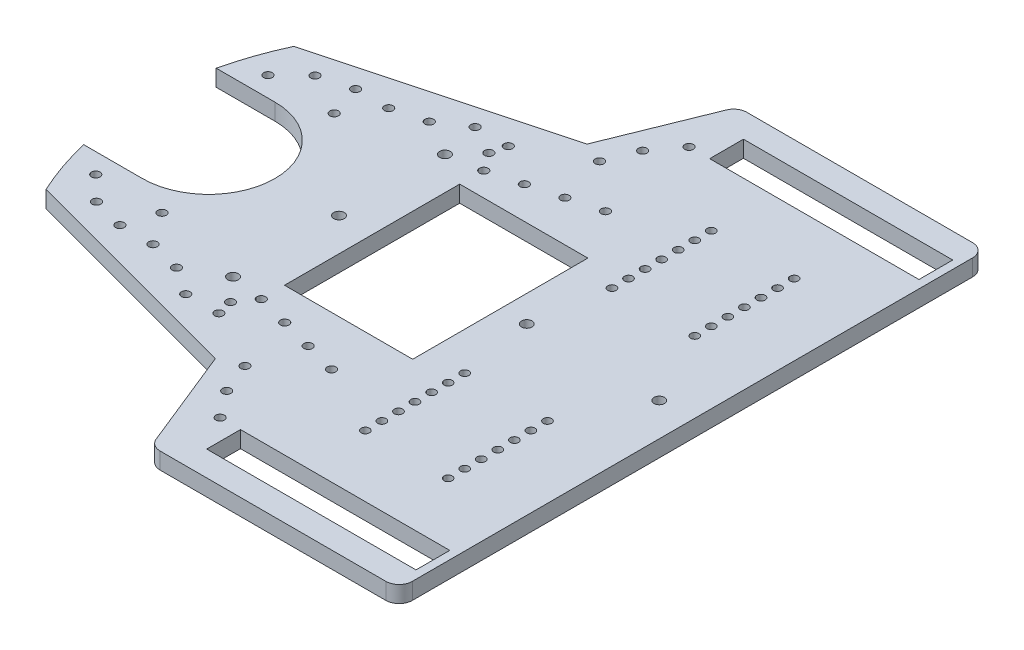
SolidWorks part; units mm, degrees
ref_plane "Front Plane" through (0, 0, 0) normal (0, 0, 1) x (1, 0, 0)
ref_plane "Top Plane" through (0, 0, 0) normal (0, 1, 0) x (1, 0, 0)
ref_plane "Right Plane" through (0, 0, 0) normal (1, 0, 0) x (0, 0, -1)
sketch "Sketch1" plane through (0, 0, 0) normal (0, 1, 0) x (1, 0, 0)
  line L0 (0, -112.5) -> (0, 0) construction
  line L1 (-3.175, 112.5) -> (95.25, 112.5)
  line L3 (-3.175, -112.5) -> (95.25, -112.5)
  line L4 (95.25, 112.5) -> (95.25, -112.5)
  line L5 (0, 0) -> (0, 112.5) construction
  arc A0 (-3.175, 112.5) -> (-3.175, -112.5) centre (-3.175, 0) ccw
  dimension "D1" = 95.25
  dimension "D4" = 112.5
  dimension "D2" = 3.175
  dimension "D3" = 225
extrude "Boss-Extrude1" add sketch "Sketch1" against normal blind 6.35
sketch "Sketch2" plane through (0, 0, 0) normal (0, 1, 0) x (1, 0, 0)
  line L0 (36.144, -66.3448) -> (36.144, -59.9948) construction
  line L1 (52.019, 0) -> (52.019, -89.9668) construction
  line L2 (11.887, -89.9668) -> (92.151, -89.9668)
  line L3 (11.887, -89.9668) -> (11.887, -102.9208)
  line L4 (11.887, -102.9208) -> (92.151, -102.9208)
  line L5 (92.151, -89.9668) -> (92.151, -102.9208)
  line L6 (11.887, 89.9668) -> (92.151, 89.9668)
  line L7 (11.887, 89.9668) -> (11.887, 102.9208)
  line L8 (11.887, 102.9208) -> (92.151, 102.9208)
  line L9 (92.151, 89.9668) -> (92.151, 102.9208)
  line L10 (52.019, 0) -> (52.019, 89.9668) construction
  line L11 (36.144, -59.9948) -> (36.144, -53.6448) construction
  line L12 (36.144, -53.6448) -> (36.144, -47.2948) construction
  line L13 (36.144, -47.2948) -> (36.144, -40.9448) construction
  line L14 (36.144, -40.9448) -> (36.144, -34.5948) construction
  line L15 (36.144, -34.5948) -> (36.144, -28.2448) construction
  line L16 (67.894, -66.3448) -> (67.894, -59.9948) construction
  line L17 (67.894, -59.9948) -> (67.894, -53.6448) construction
  line L18 (67.894, -53.6448) -> (67.894, -47.2948) construction
  line L19 (67.894, -47.2948) -> (67.894, -40.9448) construction
  line L20 (67.894, -40.9448) -> (67.894, -34.5948) construction
  line L21 (67.894, -34.5948) -> (67.894, -28.2448) construction
  line L22 (36.144, -66.3448) -> (67.894, -66.3448) construction
  line L23 (36.144, -28.2448) -> (67.894, -28.2448) construction
  line L24 (36.144, 28.2448) -> (36.144, 34.5948) construction
  line L25 (36.144, 34.5948) -> (36.144, 40.9448) construction
  line L26 (36.144, 40.9448) -> (36.144, 47.2948) construction
  line L27 (36.144, 47.2948) -> (36.144, 53.6448) construction
  line L28 (36.144, 53.6448) -> (36.144, 59.9948) construction
  line L29 (36.144, 59.9948) -> (36.144, 66.3448) construction
  line L30 (67.894, 28.2448) -> (67.894, 34.5948) construction
  line L31 (67.894, 34.5948) -> (67.894, 40.9448) construction
  line L32 (67.894, 40.9448) -> (67.894, 47.2948) construction
  line L33 (67.894, 47.2948) -> (67.894, 53.6448) construction
  line L34 (67.894, 53.6448) -> (67.894, 59.9948) construction
  line L35 (67.894, 59.9948) -> (67.894, 66.3448) construction
  line L36 (36.144, 66.3448) -> (67.894, 66.3448) construction
  line L37 (36.144, 28.2448) -> (67.894, 28.2448) construction
  line L38 (36.144, 47.2948) -> (52.019, 47.2948) construction
  line L39 (52.019, 47.2948) -> (67.894, 47.2948) construction
  line L40 (0, -112.5) -> (0, 112.5) construction
  line L41 (0, 0) -> (52.019, 0) construction
  line L42 (95.25, 112.5) -> (-3.175, 112.5) construction
  line L43 (-3.175, -112.5) -> (95.25, -112.5) construction
  line L44 (95.25, -112.5) -> (95.25, 112.5) construction
  circle A1 centre (36.144, -66.3448) radius 1.5875
  circle A2 centre (36.144, -59.9948) radius 1.5875
  circle A3 centre (36.144, -53.6448) radius 1.5875
  circle A4 centre (36.144, -47.2948) radius 1.5875
  circle A5 centre (36.144, -40.9448) radius 1.5875
  circle A6 centre (36.144, -34.5948) radius 1.5875
  circle A7 centre (36.144, -28.2448) radius 1.5875
  circle A8 centre (67.894, -66.3448) radius 1.5875
  circle A9 centre (67.894, -59.9948) radius 1.5875
  circle A10 centre (67.894, -53.6448) radius 1.5875
  circle A11 centre (67.894, -47.2948) radius 1.5875
  circle A12 centre (67.894, -40.9448) radius 1.5875
  circle A13 centre (67.894, -34.5948) radius 1.5875
  circle A14 centre (67.894, -28.2448) radius 1.5875
  circle A15 centre (36.144, 66.3448) radius 1.5875
  circle A16 centre (36.144, 59.9948) radius 1.5875
  circle A17 centre (36.144, 53.6448) radius 1.5875
  circle A18 centre (36.144, 47.2948) radius 1.5875
  circle A19 centre (36.144, 40.9448) radius 1.5875
  circle A20 centre (36.144, 34.5948) radius 1.5875
  circle A21 centre (36.144, 28.2448) radius 1.5875
  circle A22 centre (67.894, 66.3448) radius 1.5875
  circle A23 centre (67.894, 59.9948) radius 1.5875
  circle A24 centre (67.894, 53.6448) radius 1.5875
  circle A25 centre (67.894, 47.2948) radius 1.5875
  circle A26 centre (67.894, 40.9448) radius 1.5875
  circle A27 centre (67.894, 34.5948) radius 1.5875
  circle A28 centre (67.894, 28.2448) radius 1.5875
  dimension "D6" = 3.175
  dimension "D7" = 6.35
  dimension "D8" = 15.875
  dimension "D10" = 3.175
  dimension "D1" = 12.954
  dimension "D2" = 80.264
  dimension "D3" = 179.9336
  dimension "D4" = 23.622
  dimension "D5" = 15.875
  dimension "D9" = 15.875
  dimension "D11" = 6.35
  dimension "D12" = 23.622
  dimension "D13" = 56.4896
  dimension "D14" = 205.8416
  dimension "D15" = 92.151
extrude "Cut-Extrude1" cut sketch "Sketch2" against normal through all
sketch "Sketch7" plane through (0, 0, 0) normal (0, 1, 0) x (1, 0, 0)
  line L0 (46.0375, 112.5) -> (21.5519, 33.5915) construction
  line L1 (-27.5971, 33.5915) -> (21.5519, 33.5915)
  line L2 (-27.5971, 33.5915) -> (-27.5971, -33.5915)
  line L3 (-27.5971, -33.5915) -> (21.5519, -33.5915)
  line L4 (21.5519, 33.5915) -> (21.5519, -33.5915)
  line L5 (95.25, 112.5) -> (-3.175, 112.5) construction
  line L6 (21.5519, -33.5915) -> (46.0375, -112.5) construction
  line L7 (-3.175, -112.5) -> (95.25, -112.5) construction
  line L8 (-40.2971, -40.64) -> (-40.2971, 0) construction
  line L9 (-40.2971, 0) -> (-40.2971, 40.64) construction
  line L10 (95.25, -112.5) -> (95.25, 112.5) construction
  circle A0 centre (-40.2971, 0) radius 2.032
  circle A1 centre (31.7119, 0) radius 2.032
  circle A2 centre (82.5119, 0) radius 2.032
  circle A3 centre (-40.2971, 40.64) radius 2.032
  circle A4 centre (-40.2971, -40.64) radius 2.032
  dimension "D3" = 4.064
  dimension "D5" = 40.64
  dimension "D1" = 49.149
  dimension "D2" = 67.183
  dimension "D4" = 12.7
  dimension "D7" = 10.16
  dimension "D8" = 50.8
extrude "Cut-Extrude4" cut sketch "Sketch7" against normal through all
sketch "Sketch8" plane through (0, 0, 0) normal (0, 1, 0) x (1, 0, 0)
  line L0 (-3.175, 112.5) -> (-3.175, -112.5) construction
  line L1 (-115.675, 0) -> (95.25, 0) construction
  line L2 (95.25, -112.5) -> (95.25, 112.5) construction
  line L3 (-90.2716, 25.4) -> (-229.7767, 25.4)
  line L4 (-229.7767, 25.4) -> (-229.7767, -25.4)
  line L5 (-229.7767, -25.4) -> (-90.2716, -25.4)
  line L6 (-105.3846, 12.065) -> (-105.3846, -12.065) construction
  line L7 (-105.3846, -12.065) -> (-75.1586, -12.065) construction
  line L8 (-75.1586, -12.065) -> (-75.1586, 12.065) construction
  line L9 (-75.1586, 12.065) -> (-105.3846, 12.065) construction
  arc A0 (-3.175, 112.5) -> (-3.175, -112.5) centre (-3.175, 0) ccw construction
  circle A1 centre (-100.5586, 33.02) radius 1.651
  arc A2 (-90.2716, 25.4) -> (-90.2716, -25.4) centre (-90.2716, 0) cw
  circle A3 centre (-100.5586, -33.02) radius 1.651
  circle A4 centre (-75.1586, 33.02) radius 1.651
  circle A5 centre (-75.1586, -33.02) radius 1.651
  circle A6 centre (-40.2971, 0) radius 2.032 construction
  point P12 (-3.175, 0)
  point P19 (-75.1586, 0)
  point P22 (-90.2716, 12.065)
  dimension "D2" = 87.0966
  dimension "D1" = 25.4
  dimension "D6" = 33.02
  dimension "D11" = 3.302
  dimension "D3" = 112.5
  dimension "D4" = 30.226
  dimension "D5" = 24.13
  dimension "D7" = 33.02
  dimension "D8" = 33.02
  dimension "D9" = 33.02
  dimension "D10" = 25.4
extrude "Cut-Extrude5" cut sketch "Sketch8" against normal through all
sketch "Sketch9" plane through (0, 0, 0) normal (0, 1, 0) x (1, 0, 0)
  line L0 (-105.1513, 47.5087) -> (-16.4818, 71.2677)
  line L1 (-16.4818, 71.2677) -> (15.119, 149.4824)
  line L2 (-15.9904, 149.4824) -> (-132.084, 149.4824)
  line L3 (-132.084, 149.4824) -> (-132.084, 47.5087)
  line L4 (-132.084, 47.5087) -> (-105.1513, 47.5087)
  line L5 (15.119, 149.4824) -> (-15.9904, 149.4824)
  line L6 (-162.9335, 0) -> (203.9787, 0) construction
  line L7 (-105.1513, 0) -> (-105.1513, 47.5087) construction
  line L8 (-105.1513, 47.5087) -> (176.0049, 47.5087) construction
  line L9 (-16.4818, 71.2677) -> (175.2293, 71.2677) construction
  line L10 (-105.1513, -47.5087) -> (-16.4818, -71.2677)
  line L11 (-16.4818, -71.2677) -> (15.119, -149.4824)
  line L12 (15.119, -149.4824) -> (-132.084, -149.4824)
  line L13 (-132.084, -149.4824) -> (-132.084, -47.5087)
  line L14 (-132.084, -47.5087) -> (-105.1513, -47.5087)
  line L15 (-105.1513, -47.5087) -> (203.9787, -47.5087) construction
  line L16 (-16.4818, -71.2677) -> (199.2998, -71.2677) construction
  line L17 (-105.1513, -47.5087) -> (-105.1513, 0) construction
  arc A0 (-3.175, 112.5) -> (-112.7701, 25.4) centre (-3.175, 0) ccw construction
  arc A1 (-112.7701, -25.4) -> (-3.175, -112.5) centre (-3.175, 0) ccw construction
  dimension "D1" = 47.5087
  dimension "D2" = 15
  dimension "D3" = 68
  dimension "D4" = 15
  dimension "D5" = 68
extrude "Cut-Extrude6" cut sketch "Sketch9" against normal through all
fillet "Fillet1" radius 5.08 1 edges at (0.1772, -3.175, -112.5)
fillet "Fillet2" radius 5.08 3 edges at (95.25, -3.175, -112.5) (95.25, -3.175, 112.5) (0.1772, -3.175, 112.5)
sketch "Sketch10" plane through (0, 0, 0) normal (0, 1, 0) x (1, 0, 0)
  line L0 (-149.6445, 0) -> (117.1864, 0) construction
  line L1 (-91.4014, 41.91) -> (-79.1341, 45.197) construction
  line L2 (-105.1513, 47.5087) -> (-16.4818, 71.2677) construction
  line L3 (-79.1341, 45.197) -> (-66.4341, 45.197) construction
  line L4 (-66.4341, 45.197) -> (-54.1669, 48.484) construction
  line L5 (-54.1669, 48.484) -> (-43.5765, 55.4936) construction
  line L6 (-43.5765, 55.4936) -> (-30.8765, 55.4936) construction
  line L7 (-43.5765, 55.4936) -> (-32.3631, 49.5313) construction
  line L8 (-27.4372, 42.658) -> (-15.17, 45.945) construction
  line L9 (-15.17, 45.945) -> (-2.9027, 49.232) construction
  line L10 (-2.9027, 49.232) -> (9.3645, 52.519) construction
  line L11 (-30.8765, 55.4936) -> (-27.4372, 42.658) construction
  line L12 (-27.4372, 42.658) -> (8.5586, 42.658) construction
  line L13 (-8.3676, 67.9893) -> (-3.6101, 79.7646) construction
  line L14 (-3.6101, 79.7646) -> (4.033, 89.9072) construction
  line L15 (-16.4818, 71.2677) -> (-1.1064, 109.323) construction
  line L16 (-3.6101, 79.7646) -> (1.6193, 92.7078) construction
  line L17 (-8.3676, 67.9893) -> (-16.4818, 71.2677) construction
  line L18 (-91.4014, -41.91) -> (-79.1341, -45.197) construction
  line L19 (-79.1341, -45.197) -> (-66.4341, -45.197) construction
  line L20 (-66.4341, -45.197) -> (-54.1669, -48.484) construction
  line L21 (-54.1669, -48.484) -> (-43.5765, -55.4936) construction
  line L22 (-43.5765, -55.4936) -> (-30.8765, -55.4936) construction
  line L23 (-16.4818, -71.2677) -> (-105.1513, -47.5087) construction
  line L24 (-43.5765, -55.4936) -> (-32.3631, -49.5313) construction
  line L25 (-91.4014, 41.91) -> (-91.4014, 0) construction
  line L26 (-91.4014, 0) -> (-91.4014, -41.91) construction
  line L27 (-27.4383, -42.6621) -> (-15.1711, -45.9491) construction
  line L28 (-15.1711, -45.9491) -> (-2.9038, -49.2361) construction
  line L29 (-2.9038, -49.2361) -> (9.3635, -52.5231) construction
  line L30 (-27.4383, -42.6621) -> (13.4293, -42.6621) construction
  line L31 (-30.8765, -55.4936) -> (-27.4383, -42.6621) construction
  line L32 (-8.3676, -67.9893) -> (-3.6101, -79.7646) construction
  line L33 (-3.6101, -79.7646) -> (4.033, -89.9072) construction
  line L34 (-3.6101, -79.7646) -> (0.51, -89.9621) construction
  line L35 (-1.1064, -109.323) -> (-16.4818, -71.2677) construction
  line L36 (-16.4818, -71.2677) -> (-8.3676, -67.9893) construction
  line L38 (-16.4818, 71.2677) -> (-16.4818, -71.2677) construction
  circle A0 centre (-91.4014, 41.91) radius 1.651
  circle A1 centre (-79.1341, 45.197) radius 1.651
  circle A2 centre (-66.4341, 45.197) radius 1.651
  circle A3 centre (-54.1669, 48.484) radius 1.651
  circle A4 centre (-43.5765, 55.4936) radius 1.651
  circle A5 centre (-30.8765, 55.4936) radius 1.651
  circle A6 centre (-32.3631, 49.5313) radius 1.651
  circle A7 centre (-27.4372, 42.658) radius 1.651
  circle A8 centre (-15.17, 45.945) radius 1.651
  circle A9 centre (-2.9027, 49.232) radius 1.651
  circle A10 centre (9.3645, 52.519) radius 1.651
  circle A11 centre (-8.3676, 67.9893) radius 1.651
  circle A12 centre (-3.6101, 79.7646) radius 1.651
  circle A13 centre (4.033, 89.9072) radius 1.651
  circle A14 centre (-91.4014, -41.91) radius 1.651
  circle A15 centre (-79.1341, -45.197) radius 1.651
  circle A16 centre (-66.4341, -45.197) radius 1.651
  circle A17 centre (-54.1669, -48.484) radius 1.651
  circle A18 centre (-43.5765, -55.4936) radius 1.651
  circle A19 centre (-30.8765, -55.4936) radius 1.651
  circle A20 centre (-32.3631, -49.5313) radius 1.651
  circle A21 centre (-27.4383, -42.6621) radius 1.651
  circle A22 centre (-15.1711, -45.9491) radius 1.651
  circle A23 centre (-2.9038, -49.2361) radius 1.651
  circle A24 centre (9.3635, -52.5231) radius 1.651
  circle A25 centre (-8.3676, -67.9893) radius 1.651
  circle A26 centre (-3.6101, -79.7646) radius 1.651
  circle A27 centre (4.033, -89.9072) radius 1.651
  dimension "D1" = 3.302
  dimension "D6" = 3.302
  dimension "D8" = 3.302
  dimension "D11" = 3.302
  dimension "D12" = 12.7
  dimension "D15" = 3.302
  dimension "D19" = 3.302
  dimension "D2" = 41.91
  dimension "D3" = 12.7
  dimension "D4" = 18.5
  dimension "D5" = 28
  dimension "D7" = 12.7
  dimension "D9" = 12.7
  dimension "D10" = 15
  dimension "D13" = 18.5
  dimension "D14" = 28
  dimension "D16" = 12.7
  dimension "D17" = 13.2842
  dimension "D18" = 13.2884
  dimension "D20" = 12.7
  dimension "D21" = 15
  dimension "D22" = 90.394
extrude "Cut-Extrude7" cut sketch "Sketch10" against normal through all
